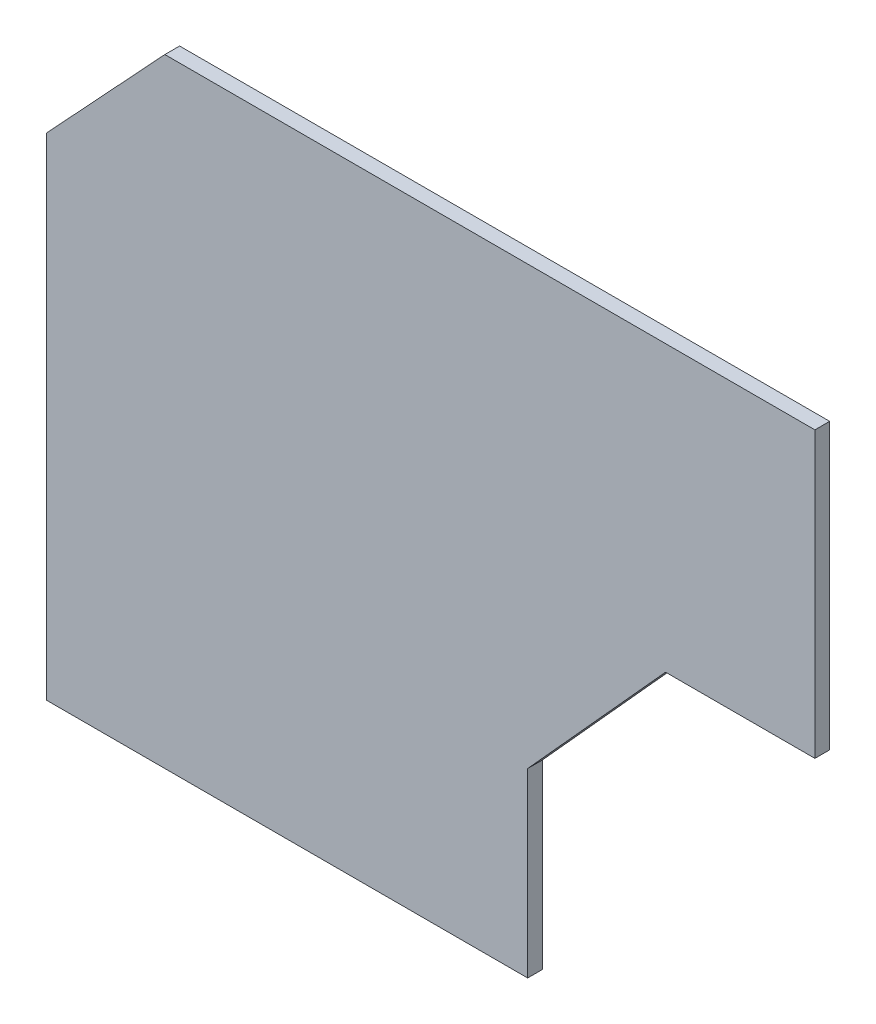
SolidWorks part; units mm, degrees
ref_plane "Alzado" through (0, 0, 0) normal (0, 0, 1) x (1, 0, 0)
ref_plane "Planta" through (0, 0, 0) normal (0, 1, 0) x (1, 0, 0)
ref_plane "Vista lateral" through (0, 0, 0) normal (1, 0, 0) x (0, 0, -1)
sketch "Croquis1" plane through (0, 0, 0) normal (0, 0, 1) x (1, 0, 0)
  line L0 (-104.012, -17.2284) -> (-87.9725, 0)
  line L1 (-87.9725, 0) -> (0, 0)
  line L2 (0, 0) -> (0, -38.5053)
  line L3 (0, -38.5053) -> (-20.2137, -38.5053)
  line L4 (-20.2137, -38.5053) -> (-38.8719, -59.1275)
  line L5 (-38.8719, -59.1275) -> (-38.8719, -83.6778)
  line L6 (-38.8719, -83.6778) -> (-104.012, -83.6778)
  line L7 (-104.012, -83.6778) -> (-104.012, -17.2284)
  point P2 (0, 0)
  point P10 (-28.5304, -28.66)
  point P11 (47.3086, -62.1888)
  point P12 (10.5865, -87.7346)
  point P13 (6.1958, -5.11)
  point P14 (-20.5474, -3.9125)
  point P15 (0, 0)
  point P17 (-12.5643, -65.382)
  point P18 (-67.6474, -31.8532)
  point P19 (-43.6983, 0)
  point P20 (-36.5135, -84.1422)
  point P21 (-20.2137, -38.5053)
  point P22 (-38.8719, -59.1275)
  point P23 (-75.861, -17.2284)
  point P24 (-87.9725, 0)
  point P25 (-104.012, -17.2284)
extrude "Saliente-Extruir1" add sketch "Croquis1" along normal blind 2
